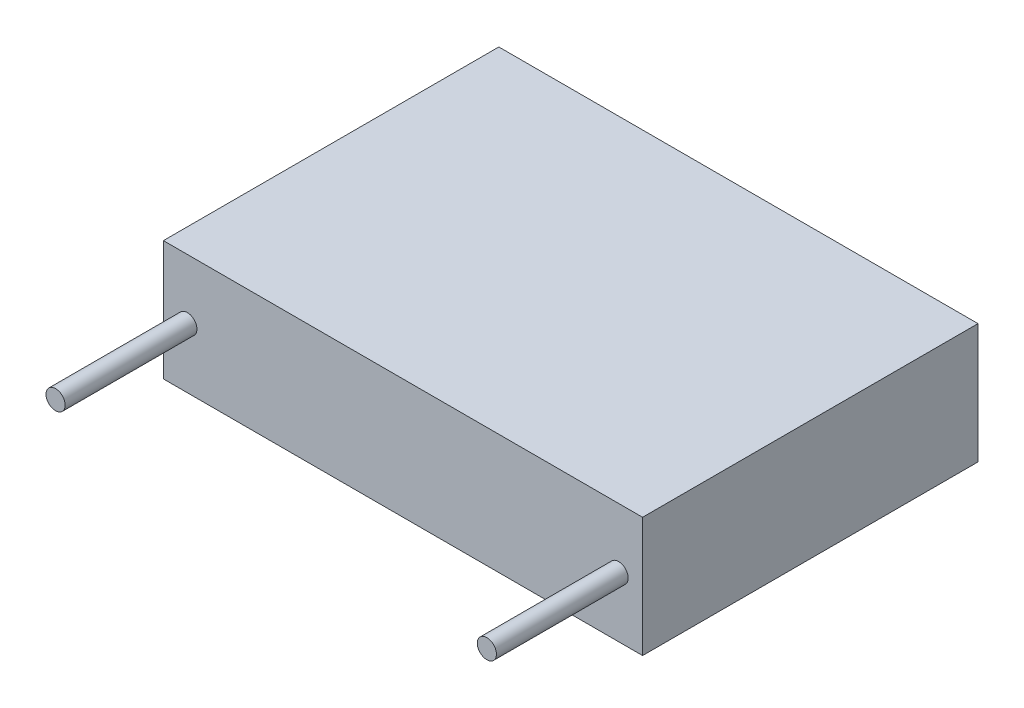
SolidWorks part; units mm, degrees
ref_plane "Спереди" through (0, 0, 0) normal (0, 0, 1) x (1, 0, 0)
ref_plane "Сверху" through (0, 0, 0) normal (0, 1, 0) x (1, 0, 0)
ref_plane "Справа" through (0, 0, 0) normal (1, 0, 0) x (0, 0, -1)
sketch "Эскиз1" plane through (0, 0, 0) normal (0, 0, 1) x (1, 0, 0)
  line L1 (0, 0) -> (20, 0)
  line L2 (0, 0) -> (0, 5)
  line L3 (0, 5) -> (20, 5)
  line L4 (20, 0) -> (20, 5)
  dimension "D1" = 5
  dimension "D2" = 20
extrude "Вытянуть1" add sketch "Эскиз1" along normal blind 14
sketch "Эскиз2" plane through (0, 0, 14) normal (0, 0, 1) x (1, 0, 0)
  line L0 (-0.6613, 2.5) -> (24.2043, 2.5) construction
  line L1 (0, 0) -> (20, 0) construction
  line L2 (20, 5) -> (0, 5) construction
  line L3 (10, 10.4113) -> (10, -0.9059) construction
  line L4 (0, 5) -> (0, 0) construction
  line L5 (20, 0) -> (20, 5) construction
  circle A0 centre (1, 2.5) radius 0.4
  circle A1 centre (19, 2.5) radius 0.4
  dimension "D1" = 18
  dimension "D2" = 0.8
extrude "Вытянуть2" add sketch "Эскиз2" along normal blind 5.5
